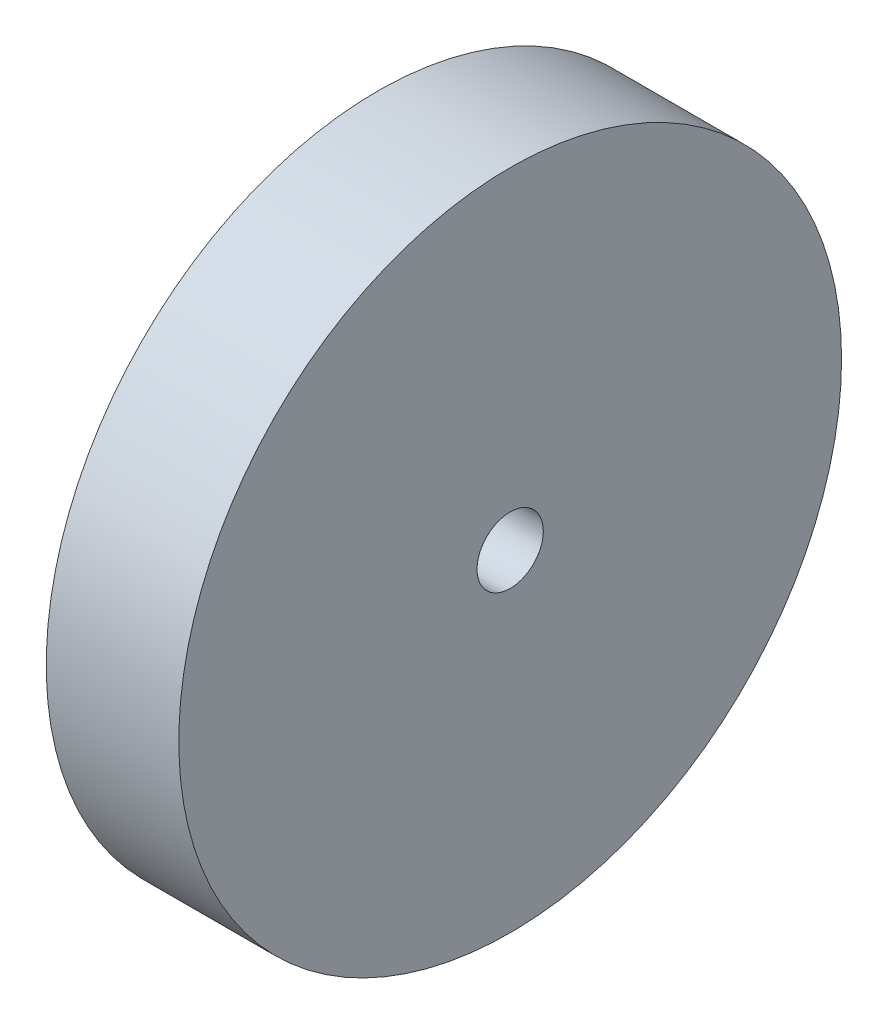
SolidWorks part; units mm, degrees
ref_plane "Front Plane" through (0, 0, 0) normal (0, 0, 1) x (1, 0, 0)
ref_plane "Top Plane" through (0, 0, 0) normal (0, 1, 0) x (1, 0, 0)
ref_plane "Right Plane" through (0, 0, 0) normal (1, 0, 0) x (0, 0, -1)
sketch "Sketch1" plane through (0, 0, 0) normal (1, 0, 0) x (0, 0, -1)
  circle A0 centre (0, 0) radius 50
  circle A1 centre (0, 0) radius 5
  dimension "D1" = 100
  dimension "D2" = 10
extrude "Boss-Extrude1" add sketch "Sketch1" along normal blind 20
